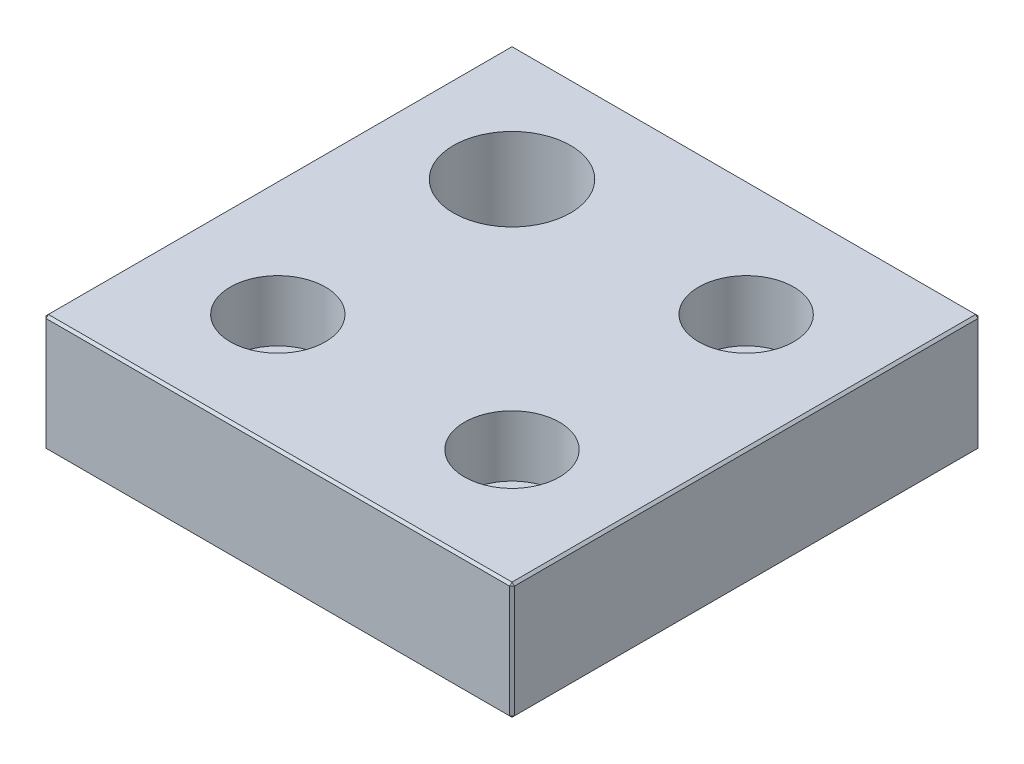
SolidWorks part; units mm, degrees
material "6061 Alloy"
ref_plane "Front Plane" through (0, 0, 0) normal (0, 0, 1) x (1, 0, 0)
ref_plane "Top Plane" through (0, 0, 0) normal (0, 1, 0) x (1, 0, 0)
ref_plane "Right Plane" through (0, 0, 0) normal (1, 0, 0) x (0, 0, -1)
sketch "Sketch1" plane through (0, 0, 0) normal (0, 1, 0) x (1, 0, 0)
  line L1 (0, 0) -> (-50.8, 0)
  line L2 (0, 0) -> (0, 50.8)
  line L3 (0, 50.8) -> (-50.8, 50.8)
  line L4 (-50.8, 0) -> (-50.8, 50.8)
  circle A0 centre (-38.1, 38.1) radius 6.35
  circle A1 centre (-12.7, 38.1) radius 3.2639
  circle A2 centre (-12.7, 12.7) radius 3.2639
  circle A3 centre (-38.1, 12.7) radius 3.2639
  dimension "D3" = 12.7
  dimension "D1" = 50.8
  dimension "D2" = 50.8
extrude "Extrude1" add sketch "Sketch1" along normal blind 12.7
sketch "Sketch2" plane through (0, 12.7, 0) normal (0, 1, 0) x (1, 0, 0)
  circle A1 centre (-12.7, 38.1) radius 5.1562
  circle A2 centre (-12.7, 12.7) radius 5.1562
  circle A3 centre (-38.1, 12.7) radius 5.1562
extrude "Cut-Extrude1" cut sketch "Sketch2" against normal blind 6.604
chamfer "Chamfer1" distance 0.254 angle 45 12 edges at (-50.8, 12.7, -25.4) (-50.8, 0, -25.4) (-25.4, 12.7, -50.8) (-50.8, 6.35, -50.8) (-25.4, 0, -50.8) (0, 12.7, -25.4) (0, 6.35, -50.8) (0, 0, -25.4) (-50.8, 6.35, 0) (-25.4, 12.7, 0) (0, 6.35, 0) (-25.4, 0, 0)
